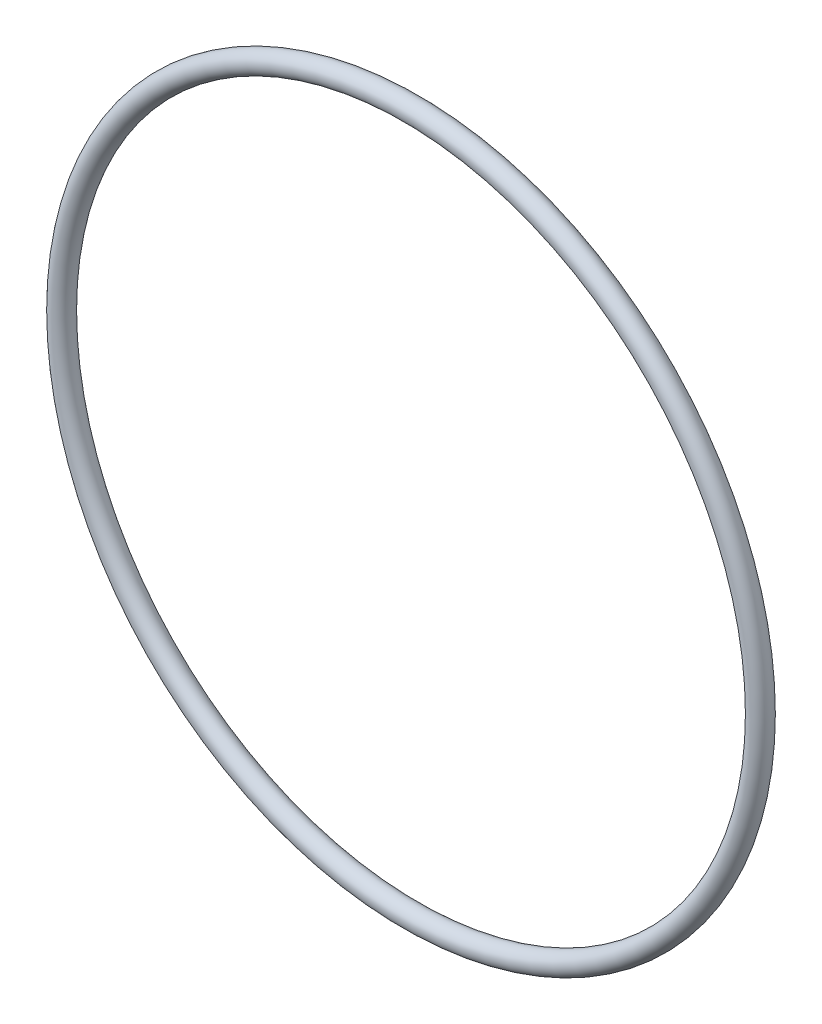
SolidWorks part; units mm, degrees
material "Rubber"
ref_plane "Front" through (0, 0, 0) normal (0, 0, 1) x (1, 0, 0)
ref_plane "Top" through (0, 0, 0) normal (0, 1, 0) x (1, 0, 0)
ref_plane "Right" through (0, 0, 0) normal (1, 0, 0) x (0, 0, -1)
sketch "Sketch1" plane through (0, 0, 0) normal (1, 0, 0) x (0, -1, 0)
  line L0 (0, -0.889) -> (0, 0.889) construction
  line L2 (-33.2346, 0) -> (33.2346, 0) construction
  line L3 (-28.4353, 0) -> (28.4353, 0) construction
  circle A0 centre (29.3243, 0) radius 0.889
  point P9 (28.4353, 0)
  point P10 (30.2133, 0)
  point P13 (29.3243, 0.889)
  point P14 (29.3243, -0.889)
  dimension "Width" = 1.778
  dimension "ID" = 56.8706
revolve "Revolve1" add sketch "Sketch1" angle 360 about L0
